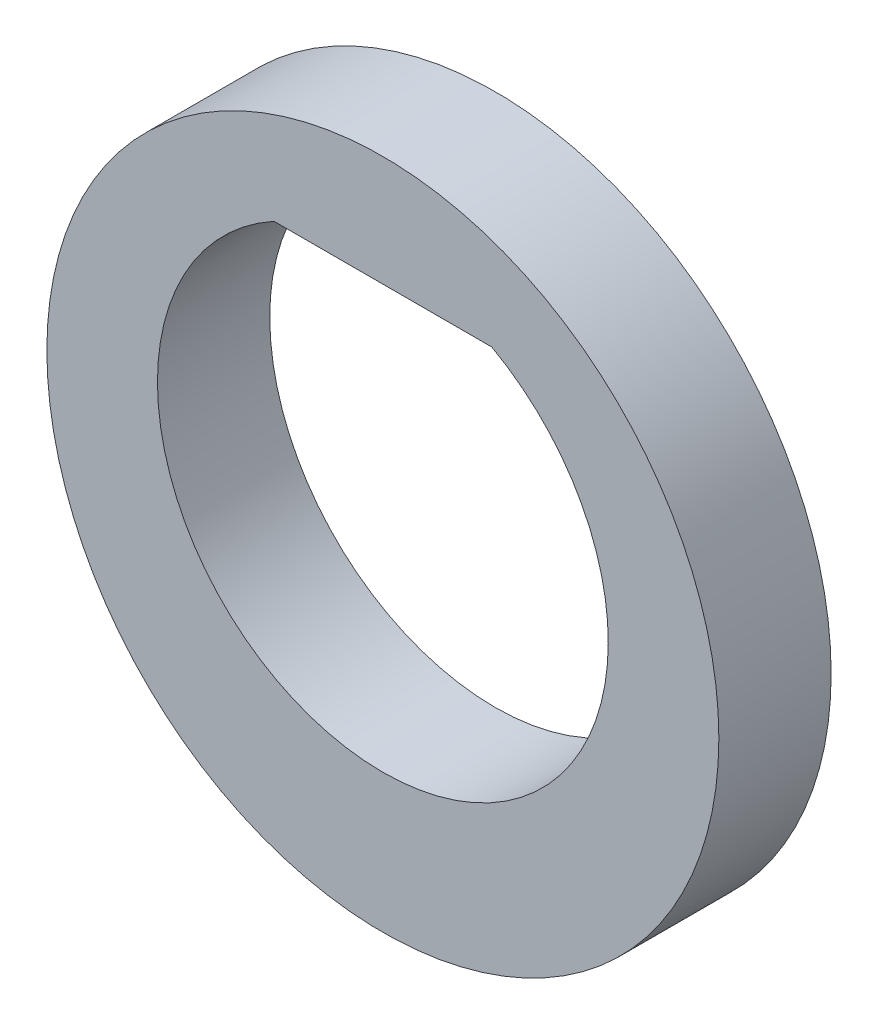
SolidWorks part; units mm, degrees
ref_plane "前视基准面" through (0, 0, 0) normal (0, 0, 1) x (1, 0, 0)
ref_plane "上视基准面" through (0, 0, 0) normal (0, 1, 0) x (1, 0, 0)
ref_plane "右视基准面" through (0, 0, 0) normal (1, 0, 0) x (0, 0, -1)
sketch "草图1" plane through (0, 0, 0) normal (0, 0, 1) x (1, 0, 0)
  line L0 (0, 0) -> (0, -0.5)
  line L1 (0, 3.515) -> (0, 3.015) construction
  line L2 (-1.9404, 3.015) -> (1.9404, 3.015)
  line L3 (0, -0.5) -> (0, -1) construction
  circle A0 centre (0, 0) radius 5.985 construction
  circle A1 centre (0, -0.5) radius 4.015 construction
  arc A2 (-1.9404, 3.015) -> (1.9404, 3.015) centre (0, -0.5) ccw
  circle A4 centre (0, -1) radius 5.985
  dimension "D1" = 0.5
  dimension "D2" = 11.97
  dimension "D3" = 8.03
  dimension "D4" = 0.5
extrude "凸台-拉伸1" add sketch "草图1" along normal blind 2 contours A0 A2 L2
